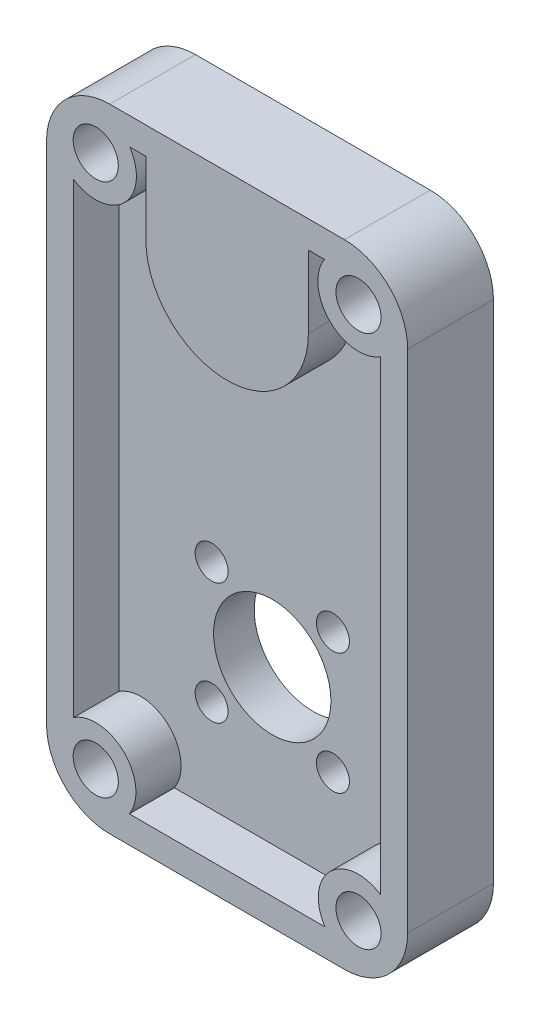
SolidWorks part; units mm, degrees
other "DetailItem1"
ref_plane "Front Plane" through (0, 0, 0) normal (0, 0, 1) x (1, 0, 0)
ref_plane "Top Plane" through (0, 0, 0) normal (0, 1, 0) x (1, 0, 0)
ref_plane "Right Plane" through (0, 0, 0) normal (1, 0, 0) x (0, 0, -1)
sketch "Sketch1" plane through (0, 0, 0) normal (0, 0, 1) x (1, 0, 0)
  line L0 (20, 0) -> (20, 70) construction
  line L1 (0, 0) -> (40, 0)
  line L2 (0, 0) -> (0, 70)
  line L3 (0, 70) -> (40, 70)
  line L4 (40, 0) -> (40, 70)
  line L5 (0, 20) -> (40, 20) construction
  line L6 (13.2825, 26.7175) -> (40, 0) construction
  line L7 (26.7175, 26.7175) -> (0, 0) construction
  circle A0 centre (20, 20) radius 9.5 construction
  circle A2 centre (26.7175, 13.2825) radius 1.825
  circle A3 centre (26.7175, 26.7175) radius 1.825
  circle A4 centre (13.2825, 26.7175) radius 1.825
  circle A5 centre (13.2825, 13.2825) radius 1.825
  circle A6 centre (20, 20) radius 6.5
  dimension "D4" = 19
  dimension "D5" = 3.65
  dimension "D6" = 13
  dimension "D1" = 70
  dimension "D2" = 40
  dimension "D3" = 20
extrude "Boss-Extrude1" add sketch "Sketch1" along normal blind 4.5
sketch "Sketch3" plane through (0, 0, 4.5) normal (0, 0, 1) x (1, 0, 0)
  line L0 (0, 0) -> (40, 0) construction
  line L1 (40, 0) -> (40, 70) construction
  line L2 (40, 70) -> (0, 70) construction
  line L3 (0, 70) -> (0, 0) construction
  line L4 (0, 0) -> (40, 0)
  line L5 (40, 0) -> (40, 70)
  line L6 (40, 70) -> (0, 70)
  line L7 (0, 70) -> (0, 0)
  line L8 (9.1648, 3) -> (30.8352, 3)
  line L9 (37, 9.1648) -> (37, 60.7754)
  line L10 (30.7754, 67) -> (29, 67)
  line L11 (3, 60.7754) -> (3, 9.1648)
  line L12 (20, 70) -> (20, 0) construction
  line L13 (3, 59) -> (37, 59) construction
  line L14 (11, 59) -> (11, 67)
  line L15 (29, 59) -> (29, 67)
  line L16 (11, 67) -> (9.2246, 67)
  line L17 (37, 67) -> (3, 67) construction
  line L18 (3, 67) -> (3, 3) construction
  line L19 (37, 3) -> (37, 67) construction
  line L20 (3, 3) -> (37, 3) construction
  circle A0 centre (20, 59) radius 7 construction
  arc A1 (11, 59) -> (29, 59) centre (20, 59) ccw
  circle A2 centre (20, 59) radius 9 construction
  circle A3 centre (5.45, 64.55) radius 2.45 construction
  arc A4 (3, 60.7754) -> (9.2246, 67) centre (5.45, 64.55) ccw
  arc A8 (9.1648, 3) -> (3, 9.1648) centre (5.45, 5.45) ccw
  arc A9 (30.8352, 3) -> (37, 9.1648) centre (34.55, 5.45) cw
  arc A10 (37, 60.7754) -> (30.7754, 67) centre (34.55, 64.55) cw
  dimension "D3" = 14
  dimension "D5" = 4.9
  dimension "D6" = 9
  dimension "D2" = 11
  dimension "D1" = 3
  dimension "D4" = 2
extrude "Boss-Extrude2" add sketch "Sketch3" along normal blind 5
sketch "Sketch6" plane through (0, 0, 9.5) normal (0, 0, 1) x (1, 0, 0)
  arc A0 (9.1648, 3) -> (3, 9.1648) centre (5.45, 5.45) ccw construction
  arc A1 (37, 9.1648) -> (30.8352, 3) centre (34.55, 5.45) ccw construction
  arc A2 (30.7754, 67) -> (37, 60.7754) centre (34.55, 64.55) ccw construction
  arc A3 (3, 60.7754) -> (9.2246, 67) centre (5.45, 64.55) ccw construction
  arc A4 (9.1648, 3) -> (3, 9.1648) centre (5.45, 5.45) ccw construction
  arc A5 (37, 9.1648) -> (30.8352, 3) centre (34.55, 5.45) ccw construction
  arc A6 (30.7754, 67) -> (37, 60.7754) centre (34.55, 64.55) ccw construction
  arc A7 (3, 60.7754) -> (9.2246, 67) centre (5.45, 64.55) ccw construction
  circle A8 centre (5.45, 64.55) radius 2.5
  circle A9 centre (5.45, 5.45) radius 2.5
  circle A10 centre (34.55, 5.45) radius 2.5
  circle A11 centre (34.55, 64.55) radius 2.5
  dimension "D1" = 5
extrude "Cut-Extrude3" cut sketch "Sketch6" against normal blind 7
ref_plane "Mid Plane - Length" through (20, 0, 0) normal (1, 0, 0) x (0, 0, -1)
ref_plane "Mid Plane - Width" through (0, 35, 0) normal (0, -1, 0) x (-1, 0, 0)
sketch "Sketch4" plane through (0, 0, 0) normal (0, 0, -1) x (-1, 0, 0)
  line L0 (-20, 70) -> (-20, 0) construction
  line L1 (-40, 70) -> (0, 70) construction
  line L2 (0, 0) -> (-40, 0) construction
  line L3 (-40, 66) -> (0, 66) construction
  line L4 (-40, 0) -> (-40, 70) construction
  line L5 (0, 70) -> (0, 0) construction
  line L6 (-40, 59) -> (0, 59) construction
  circle A0 centre (-20, 59) radius 7
  dimension "D3" = 14
  dimension "D1" = 4
  dimension "D2" = 7
extrude "Cut-Extrude1" cut sketch "Sketch4" against normal offset from surface (7.5 mm away) 2 up to face at (37.05, 64.55, 9.5)
sketch "Sketch5" plane through (0, 0, 0) normal (0, 0, -1) x (-1, 0, 0)
  line L0 (-20, 70) -> (-20, 39.0054) construction
  line L1 (-40, 70) -> (0, 70) construction
  arc A0 (-7.5811, 47.3088) -> (-32.9371, 47.0672) centre (-20, 20) ccw construction
  text T0 "4108" font "Century Gothic" height 6.25
  dimension "D1" = 50
extrude "Text-4108" [suppressed] cut sketch "Sketch5" against normal blind 1
fillet "Fillet1" radius 7 4 edges at (40, 70, 4.75) (0, 70, 4.75) (0, 0, 4.75) (40, 0, 4.75)
sketch "Sketch9" plane through (0, 0, 0) normal (0, 0, -1) x (-1, 0, 0)
  arc A0 (-6.2895, 46.6837) -> (-33.9585, 46.5549) centre (-20, 20) ccw construction
  text T0 "2804" font "Century Gothic" height 6
extrude "Text-2804" cut sketch "Sketch9" against normal blind 1
